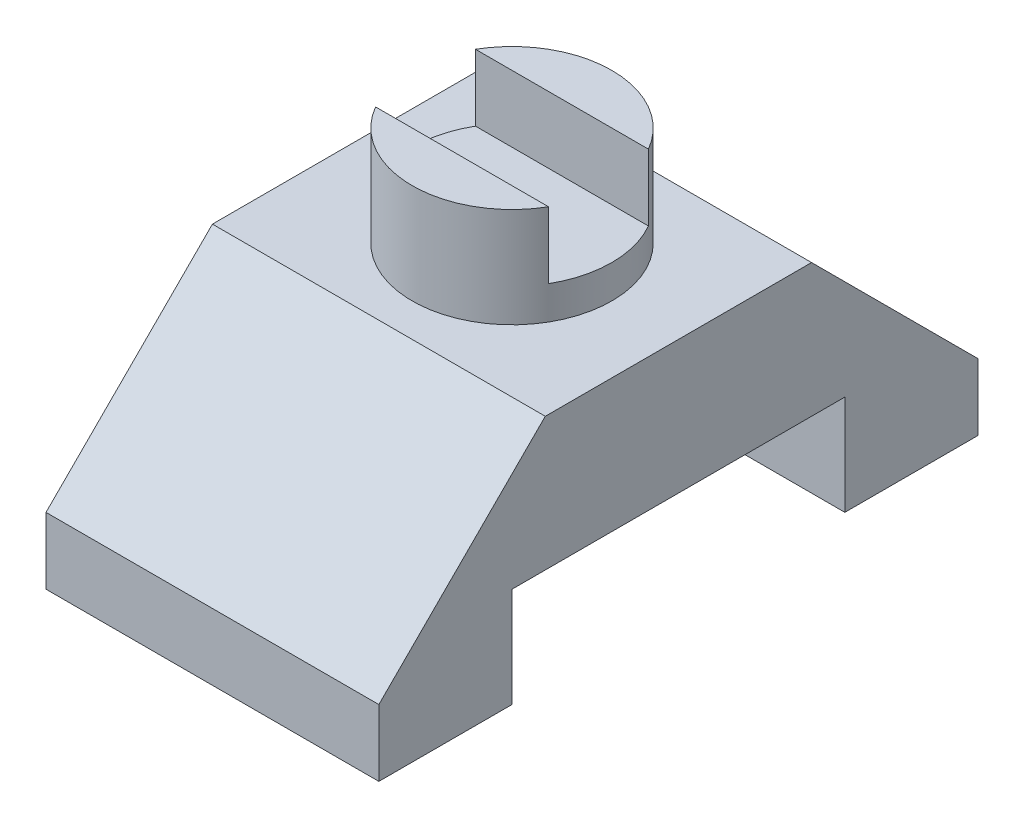
SolidWorks part; units mm, degrees
ref_plane "Alzado" through (0, 0, 0) normal (0, 0, 1) x (1, 0, 0)
ref_plane "Planta" through (0, 0, 0) normal (0, 1, 0) x (1, 0, 0)
ref_plane "Vista lateral" through (0, 0, 0) normal (1, 0, 0) x (0, 0, -1)
sketch "Croquis2" plane through (0, 0, 0) normal (1, 0, 0) x (0, 0, -1)
  line L0 (-45, 0) -> (-25, 0)
  line L1 (-25, 0) -> (-25, 15)
  line L2 (-25, 15) -> (25, 15)
  line L3 (25, 15) -> (25, 0)
  line L4 (25, 0) -> (45, 0)
  line L5 (45, 0) -> (45, 10)
  line L6 (45, 10) -> (20, 35)
  line L7 (20, 35) -> (-20, 35)
  line L8 (-20, 35) -> (-45, 10)
  line L9 (-45, 10) -> (-45, 0)
  point P3 (0, 15)
  point P12 (0, 35)
  dimension "D1" = 15
  dimension "D2" = 50
  dimension "D3" = 90
  dimension "D4" = 10
  dimension "D5" = 25
  dimension "D6" = 40
extrude "Saliente-Extruir1" add sketch "Croquis2" along normal mid plane 50
sketch "Croquis3" plane through (0, 0, 0) normal (1, 0, 0) x (0, 0, -1)
  line L0 (0, -6.407) -> (0, 62.633) construction
  line L1 (0, 35) -> (15, 35)
  line L2 (20, 35) -> (-20, 35) construction
  line L3 (15, 35) -> (15, 50)
  line L4 (15, 50) -> (7.5, 50)
  line L5 (7.5, 50) -> (7.5, 40)
  line L6 (7.5, 40) -> (0, 40)
  line L7 (0, 40) -> (0, 35)
  line L8 (25, 0) -> (45, 0) construction
  dimension "D1" = 15
  dimension "D2" = 7.5
  dimension "D3" = 10
  dimension "D4" = 50
revolve "Revolución2" add sketch "Croquis3" angle 360 about L0
sketch "Croquis5" plane through (0, 0, 0) normal (1, 0, 0) x (0, 0, -1)
  line L0 (15, 50) -> (-15, 50) construction
  line L1 (-7.5, 50) -> (7.5, 50)
  line L2 (-7.5, 50) -> (-7.5, 40)
  line L3 (-7.5, 40) -> (7.5, 40)
  line L4 (7.5, 50) -> (7.5, 40)
  point P4 (0, 40)
  dimension "D1" = 15
  dimension "D2" = 10
extrude "Cortar-Extruir1" cut sketch "Croquis5" against normal up to next and the other way up to next
